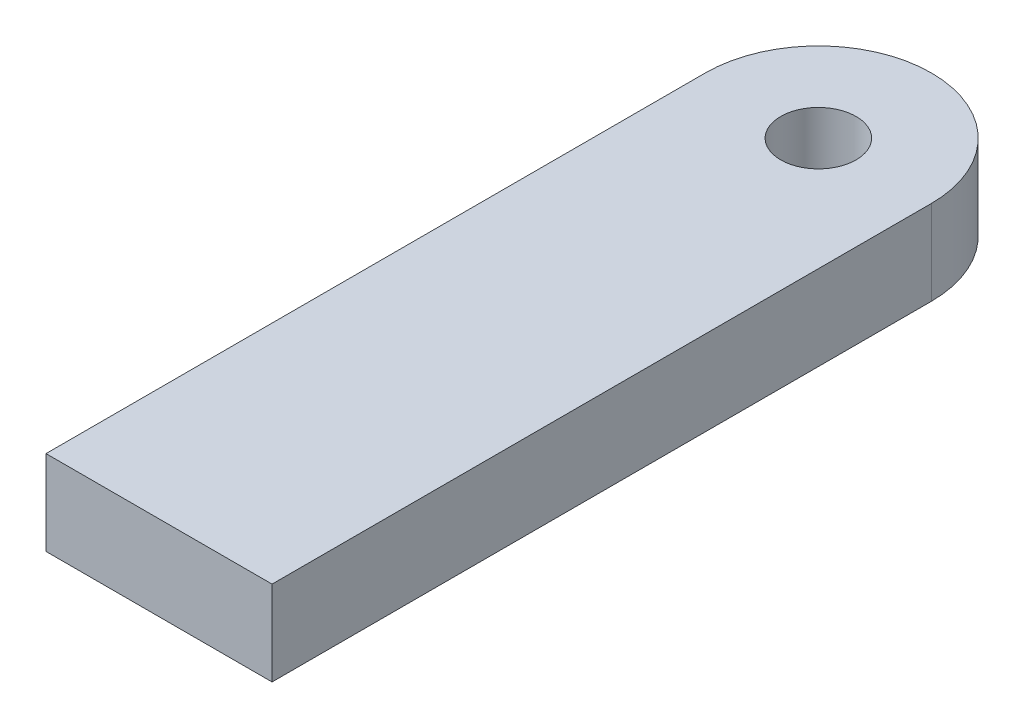
SolidWorks part; units mm, degrees
ref_plane "Plan de face" through (0, 0, 0) normal (0, 0, 1) x (1, 0, 0)
ref_plane "Plan de dessus" through (0, 0, 0) normal (0, 1, 0) x (1, 0, 0)
ref_plane "Plan de droite" through (0, 0, 0) normal (1, 0, 0) x (0, 0, -1)
sketch "Esquisse1" plane through (0, 0, 0) normal (0, 1, 0) x (1, 0, 0)
  line L1 (-12, -35) -> (12, -35)
  line L2 (-12, -35) -> (-12, 35)
  line L4 (12, -35) -> (12, 35)
  line L5 (-12, -35) -> (12, 35) construction
  line L6 (-12, 35) -> (12, -35) construction
  circle A0 centre (0, 35) radius 4
  arc A1 (12, 35) -> (-12, 35) centre (0, 35) ccw
  point P0 (0, 0)
  dimension "D1" = 24
  dimension "D2" = 70
extrude "Boss.-Extru.1" add sketch "Esquisse1" along normal blind 9
